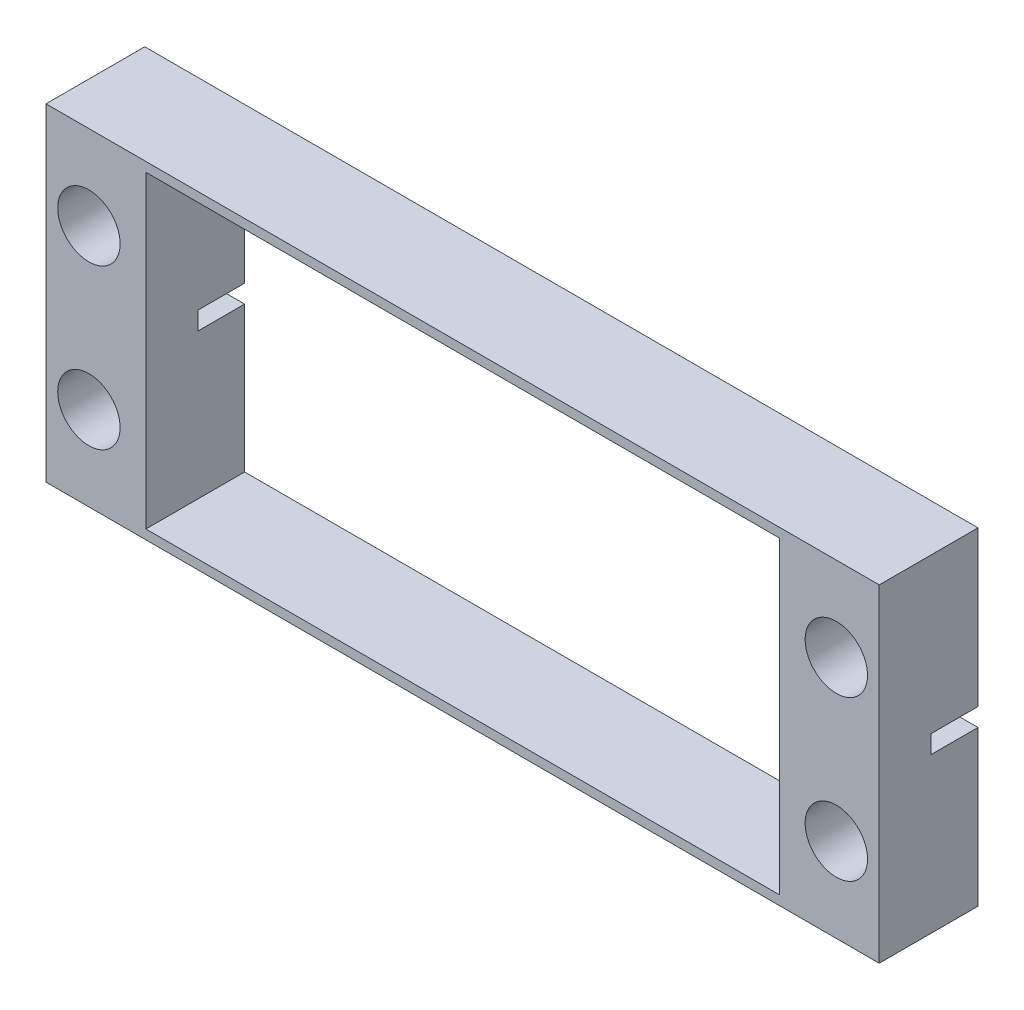
SolidWorks part; units mm, degrees
ref_plane "Front Plane" through (0, 0, 0) normal (0, 0, 1) x (1, 0, 0)
ref_plane "Top Plane" through (0, 0, 0) normal (0, 1, 0) x (1, 0, 0)
ref_plane "Right Plane" through (0, 0, 0) normal (1, 0, 0) x (0, 0, -1)
sketch "Sketch1" plane through (0, 0, 0) normal (0, 0, 1) x (1, 0, 0)
  line L1 (-26.7, -10.5) -> (26.7, -10.5)
  line L2 (-26.7, -10.5) -> (-26.7, 10.5)
  line L3 (-26.7, 10.5) -> (26.7, 10.5)
  line L4 (26.7, -10.5) -> (26.7, 10.5)
  line L5 (-26.7, -10.5) -> (26.7, 10.5) construction
  line L6 (-26.7, 10.5) -> (26.7, -10.5) construction
  point P0 (0, 0)
  dimension "D1" = 53.4
  dimension "D2" = 21
extrude "Boss-Extrude2" add sketch "Sketch1" along normal blind 6.33
sketch "Sketch3" plane through (0, 0, 6.33) normal (0, 0, 1) x (1, 0, 0)
  line L0 (0, 0) -> (0, 17.1102) construction
  line L1 (0, 0) -> (32.4612, 0) construction
  line L3 (-20.3, -9.9) -> (20.3, -9.9)
  line L4 (-20.3, -9.9) -> (-20.3, 9.9)
  line L5 (-20.3, 9.9) -> (20.3, 9.9)
  line L6 (20.3, -9.9) -> (20.3, 9.9)
  line L7 (-20.3, -9.9) -> (20.3, 9.9) construction
  line L8 (-20.3, 9.9) -> (20.3, -9.9) construction
  line L9 (-26.7, 10.5) -> (-26.7, -10.5) construction
  line L10 (26.7, 10.5) -> (-26.7, 10.5) construction
  dimension "D1" = 6.4
  dimension "D2" = 0.6
extrude "Cut-Extrude1" cut sketch "Sketch3" against normal through all
sketch "Sketch4" plane through (-26.7, 0, 0) normal (-1, 0, 0) x (0, 0, 1)
  line L0 (0, 0) -> (9.4697, 0) construction
  line L1 (0, 0.58) -> (3, 0.58)
  line L2 (0, 10.5) -> (0, -10.5) construction
  line L3 (3, 0.58) -> (3, -0.58)
  line L4 (0, 0.58) -> (0, -0.58)
  line L5 (0, -0.58) -> (3, -0.58)
  point P10 (3, 0)
  dimension "D1" = 3
  dimension "D2" = 0.58
extrude "Cut-Extrude2" cut sketch "Sketch4" against normal through all
sketch "Sketch5" plane through (0, 0, 6.33) normal (0, 0, 1) x (1, 0, 0)
  line L0 (0, 0) -> (0, 41.3476) construction
  line L1 (0, 0) -> (29.193, 0) construction
  circle A0 centre (-23.95, 5.1) radius 2
  circle A1 centre (-23.95, -5.1) radius 2
  circle A2 centre (23.95, -5.1) radius 2
  circle A3 centre (23.95, 5.1) radius 2
  point P12 (-21.95, 5.1)
  point P13 (21.95, 5.1)
  dimension "D2" = 4
  dimension "D1" = 10.2
  dimension "D3" = 43.9
extrude "Cut-Extrude3" cut sketch "Sketch5" against normal blind 6.33
